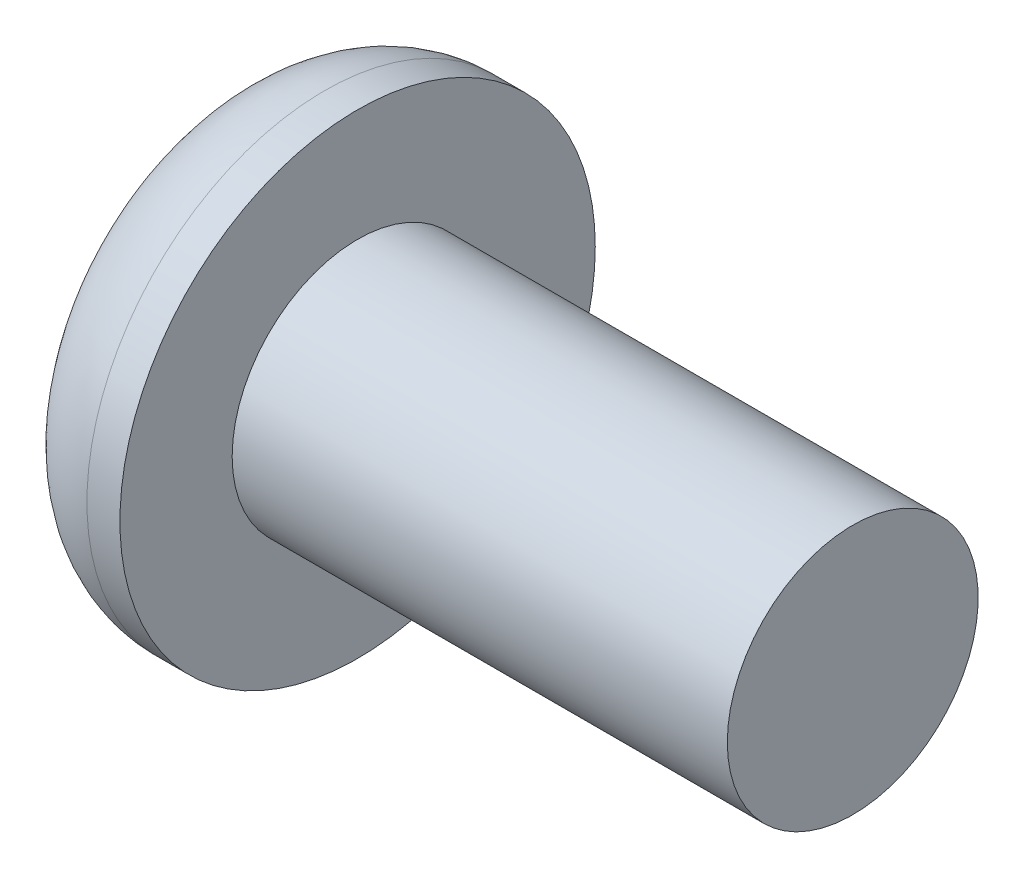
SolidWorks part; units mm, degrees
ref_plane "Front" through (0, 0, 0) normal (0, 0, 1) x (1, 0, 0)
ref_plane "Top" through (0, 0, 0) normal (0, 1, 0) x (1, 0, 0)
ref_plane "Right" through (0, 0, 0) normal (1, 0, 0) x (0, 0, -1)
sketch "Sketch1" plane through (0, 0, 0) normal (1, 0, 0) x (0, 0, -1)
  circle A0 centre (0, 0) radius 4.572
  dimension "D1" = 9.144
extrude "Boss-Extrude1" add sketch "Sketch1" along normal blind 2.54
sketch "Sketch2" plane through (2.54, 0, 0) normal (1, 0, 0) x (0, 0, -1)
  circle A0 centre (0, 0) radius 2.413
  dimension "D1" = 4.826
extrude "Boss-Extrude2" add sketch "Sketch2" along normal blind 9.525
fillet "Fillet1" radius 1.905 1 edges at (0, 0, -4.572)
sketch "Sketch3" plane through (0, 0, 0) normal (-1, 0, 0) x (0, 0, 1)
  line L1 (1.5736, -0.9402) -> (1.601, 0.8927)
  line L2 (1.601, 0.8927) -> (0.0274, 1.8329)
  line L3 (0.0274, 1.8329) -> (-1.5736, 0.9402)
  line L4 (-1.5736, 0.9402) -> (-1.601, -0.8927)
  line L5 (-1.601, -0.8927) -> (-0.0274, -1.8329)
  line L6 (-0.0274, -1.8329) -> (1.5736, -0.9402)
  circle A0 centre (0, 0) radius 1.5875 construction
extrude "Cut-Extrude1" cut sketch "Sketch3" against normal blind 1.905
